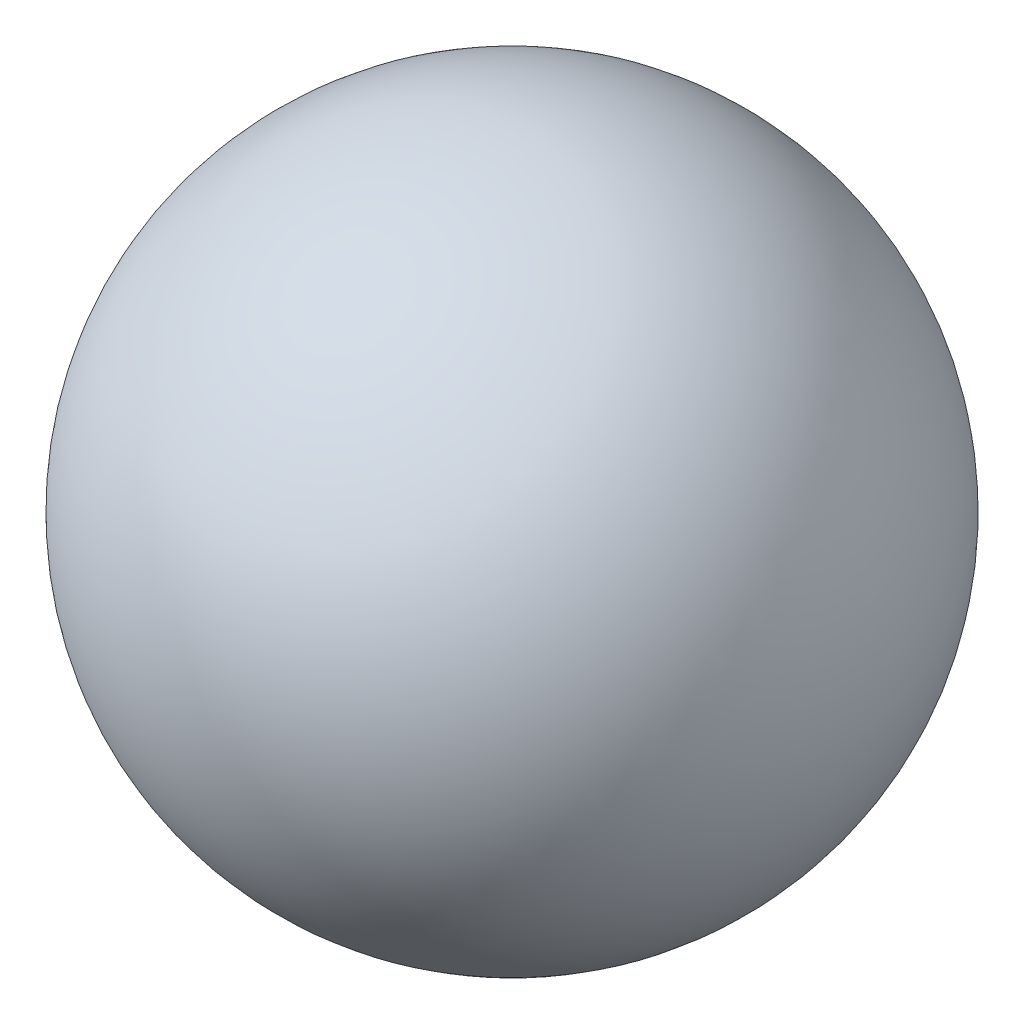
SolidWorks part; units mm, degrees
ref_plane "Plan de face" through (0, 0, 0) normal (0, 0, 1) x (1, 0, 0)
ref_plane "Plan de dessus" through (0, 0, 0) normal (0, 1, 0) x (1, 0, 0)
ref_plane "Plan de droite" through (0, 0, 0) normal (1, 0, 0) x (0, 0, -1)
sketch "Esquisse1" plane through (0, 0, 0) normal (0, 0, 1) x (1, 0, 0)
  line L0 (0, 5) -> (0, 0) construction
  line L1 (0, 5) -> (0, 4)
  line L2 (-1.5, -3.7081) -> (-1.5, -4.7697)
  arc A0 (-1.5, -4.7697) -> (0, 5) centre (0, 0) cw
  arc A1 (0, 4) -> (-1.5, -3.7081) centre (0, 0) ccw
  dimension "D1" = 5
  dimension "D2" = 1
  dimension "D3" = 1.5
revolve "Révolution1" add sketch "Esquisse1" angle 360 about L0
